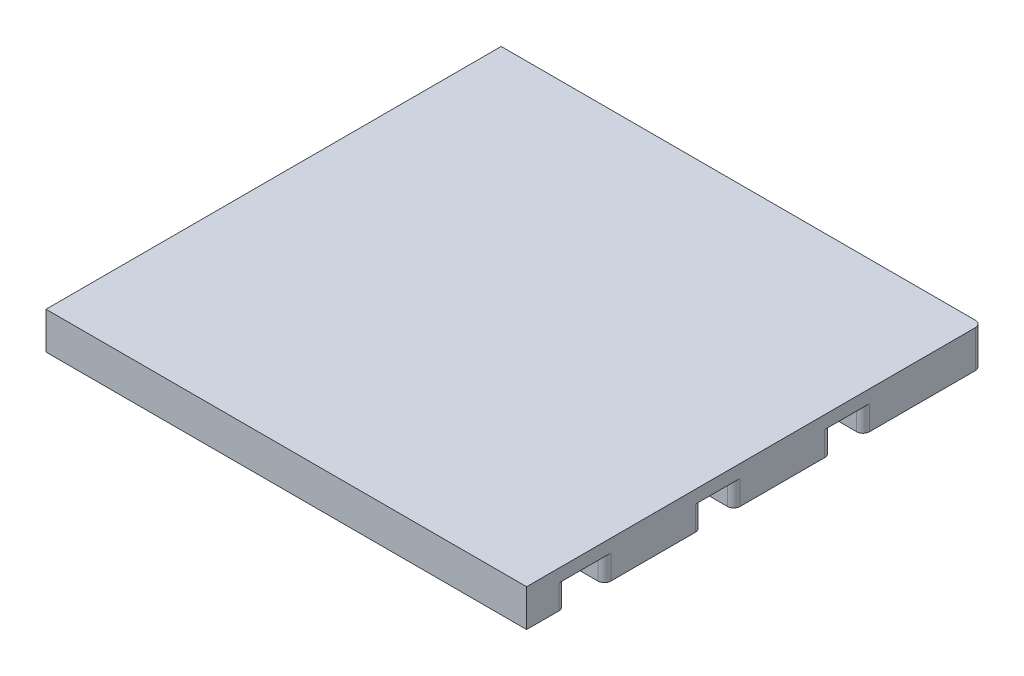
SolidWorks part; units mm, degrees
ref_plane "Front Plane" through (0, 0, 0) normal (0, 0, 1) x (1, 0, 0)
ref_plane "Top Plane" through (0, 0, 0) normal (0, 1, 0) x (1, 0, 0)
ref_plane "Right Plane" through (0, 0, 0) normal (1, 0, 0) x (0, 0, -1)
sketch "Sketch3" plane through (0, 0, 0) normal (0, 1, 0) x (1, 0, 0)
  line L1 (0, 0) -> (149, 0)
  line L2 (0, 0) -> (0, -141.12)
  line L3 (0, -141.12) -> (149, -141.12)
  line L4 (149, 0) -> (149, -141.12)
  dimension "D1" = 141.12
  dimension "D2" = 149
extrude "Boss-Extrude1" add sketch "Sketch3" along normal blind 4
sketch "Sketch5" plane through (0, 4, 0) normal (0, 1, 0) x (1, 0, 0)
  line L0 (0, 0) -> (0, -141.12) construction
  line L1 (149, 0) -> (82, 0)
  line L2 (149, 0) -> (149, -36.8)
  line L3 (149, -36.8) -> (82, -36.8)
  line L4 (82, 0) -> (82, -36.8)
  line L5 (0, -9.9) -> (67, -9.9)
  line L6 (0, -9.9) -> (0, -40.1)
  line L7 (0, -40.1) -> (67, -40.1)
  line L8 (67, -9.9) -> (67, -40.1)
  line L9 (149, 0) -> (0, 0) construction
  line L10 (149, -141.12) -> (149, 0) construction
  line L11 (0, -50) -> (67, -50)
  line L12 (0, -50) -> (0, -80.2)
  line L13 (0, -80.2) -> (67, -80.2)
  line L14 (67, -50) -> (67, -80.2)
  line L15 (0, -90.1) -> (67, -90.1)
  line L16 (0, -90.1) -> (0, -120.3)
  line L17 (0, -120.3) -> (67, -120.3)
  line L18 (67, -90.1) -> (67, -120.3)
  line L19 (149, -46.7) -> (82, -46.7)
  line L20 (149, -46.7) -> (149, -76.9)
  line L21 (149, -76.9) -> (82, -76.9)
  line L22 (82, -46.7) -> (82, -76.9)
  line L23 (12.85, -9.9) -> (12.85, -24.2) construction
  line L24 (149, -86.8) -> (82, -86.8)
  line L25 (149, -86.8) -> (149, -117)
  line L26 (149, -117) -> (82, -117)
  line L27 (82, -86.8) -> (82, -117)
  line L28 (12.85, -24.2) -> (12.85, -27.8) construction
  line L29 (12.85, -27.8) -> (12.85, -40.1) construction
  line L30 (12.85, -24.2) -> (40.15, -24.2)
  line L31 (12.85, -27.8) -> (40.15, -27.8)
  line L32 (12.85, -50) -> (12.85, -64.3) construction
  line L33 (12.85, -64.3) -> (12.85, -67.9) construction
  line L34 (12.85, -67.9) -> (12.85, -80.2) construction
  line L35 (12.85, -64.3) -> (40.15, -64.3)
  line L36 (12.85, -67.9) -> (40.15, -67.9)
  line L37 (97.3, -36.8) -> (97.3, -24.5) construction
  line L38 (97.3, -24.5) -> (97.3, -20.9) construction
  line L39 (97.3, -20.9) -> (97.3, 0) construction
  line L40 (97.3, -20.9) -> (124.6, -20.9)
  line L41 (97.3, -24.5) -> (124.6, -24.5)
  line L42 (97.3, -46.7) -> (97.3, -61) construction
  line L43 (97.3, -61) -> (97.3, -64.6) construction
  line L44 (97.3, -64.6) -> (97.3, -76.9) construction
  line L45 (97.3, -61) -> (124.6, -61)
  line L46 (97.3, -64.6) -> (124.6, -64.6)
  line L47 (12.85, -90.1) -> (12.85, -104.4) construction
  line L48 (12.85, -104.4) -> (12.85, -108) construction
  line L49 (12.85, -108) -> (12.85, -120.3) construction
  line L50 (12.85, -104.4) -> (40.15, -104.4)
  line L51 (12.85, -108) -> (40.15, -108)
  line L52 (97.3, -86.8) -> (97.3, -101.1) construction
  line L53 (97.3, -101.1) -> (97.3, -104.7) construction
  line L54 (97.3, -104.7) -> (97.3, -117) construction
  line L55 (97.3, -101.1) -> (124.6, -101.1)
  line L56 (97.3, -104.7) -> (124.6, -104.7)
  arc A0 (12.85, -27.8) -> (12.85, -24.2) centre (12.85, -26) cw
  arc A1 (40.15, -24.2) -> (40.15, -27.8) centre (40.15, -26) cw
  arc A2 (12.85, -64.3) -> (12.85, -67.9) centre (12.85, -66.1) ccw
  arc A3 (40.15, -64.3) -> (40.15, -67.9) centre (40.15, -66.1) cw
  arc A4 (97.3, -24.5) -> (97.3, -20.9) centre (97.3, -22.7) cw
  arc A5 (124.6, -20.9) -> (124.6, -24.5) centre (124.6, -22.7) cw
  arc A6 (97.3, -64.6) -> (97.3, -61) centre (97.3, -62.8) cw
  arc A7 (124.6, -61) -> (124.6, -64.6) centre (124.6, -62.8) cw
  arc A8 (12.85, -104.4) -> (12.85, -108) centre (12.85, -106.2) ccw
  arc A9 (40.15, -104.4) -> (40.15, -108) centre (40.15, -106.2) cw
  arc A10 (97.3, -101.1) -> (97.3, -104.7) centre (97.3, -102.9) ccw
  arc A11 (124.6, -101.1) -> (124.6, -104.7) centre (124.6, -102.9) cw
  line M18 (0, 0) -> (0, -141.12)
  line M20 (149, -141.12) -> (149, 0)
  line M21 (149, 0) -> (0, 0)
  dimension "D1" = 67
  dimension "D2" = 36.8
  dimension "D3" = 67
  dimension "D4" = 30.2
  dimension "D5" = 9.9
  dimension "D6" = 30.2
  dimension "D7" = 9.9
  dimension "D8" = 9.9
  dimension "D9" = 30.2
  dimension "D10" = 9.9
  dimension "D11" = 30.2
  dimension "D12" = 9.9
  dimension "D13" = 30.2
  dimension "D14" = 67
  dimension "D15" = 67
  dimension "D16" = 67
  dimension "D17" = 67
  dimension "D18" = 14.3
  dimension "D19" = 12.3
  dimension "D20" = 12.85
  dimension "D21" = 27.3
  dimension "D22" = 14.3
  dimension "D23" = 12.3
  dimension "D24" = 27.3
  dimension "D25" = 3.6
  dimension "D26" = 12.3
  dimension "D27" = 24.4
  dimension "D28" = 27.3
  dimension "D29" = 12.3
  dimension "D30" = 14.3
  dimension "D31" = 14.3
  dimension "D32" = 12.3
  dimension "D33" = 14.3
  dimension "D34" = 12.3
extrude "Boss-Extrude2" add sketch "Sketch5" against normal blind 11.55 contours L8 L5 L7 L30 A1 L31 A0 M18 | L4 L3 L40 A5 L41 A4 M21 M20 | L14 L11 L13 L35 A3 L36 A2 M18 | L19 L22 L21 L45 A7 L46 A6 M20 | L18 L15 L17 L50 A9 L51 A8 M18 | L24 L27 L26 L55 A11 L56 A10 M20
fillet "Fillet1" radius 2 24 edges at (149, -3.775, 86.8) (82, -3.775, 86.8) (149, -3.775, 117) (82, -3.775, 117) (67, -3.775, 90.1) (67, -3.775, 120.3) (0, -3.775, 120.3) (0, -3.775, 90.1) (0, -3.775, 80.2) (82, -3.775, 76.9) (149, -3.775, 76.9) (149, -3.775, 46.7) (82, -3.775, 46.7) (67, -3.775, 50) (67, -3.775, 80.2) (0, -3.775, 50) (0, -3.775, 40.1) (67, -3.775, 40.1) (82, -3.775, 36.8) (149, -3.775, 36.8) (149, -1.775, 0) (82, -3.775, 0) (67, -3.775, 9.9) (0, -3.775, 9.9)
sketch "Sketch6" plane through (0, 0, 0) normal (0, -1, 0) x (1, 0, 0)
  line L0 (0, 129.12) -> (149, 129.12)
  line L1 (0, 118.3) -> (0, 141.12) construction
  line L2 (149, 141.12) -> (149, 115) construction
  line L3 (149, 129.12) -> (149, 141.12)
  line L4 (149, 141.12) -> (0, 141.12)
  line L5 (0, 141.12) -> (0, 129.12)
  dimension "D1" = 12
extrude "Boss-Extrude3" add sketch "Sketch6" along normal blind 7.5
fillet "Fillet2" radius 2 2 edges at (149, -3.75, 129.12) (0, -3.75, 129.12)
